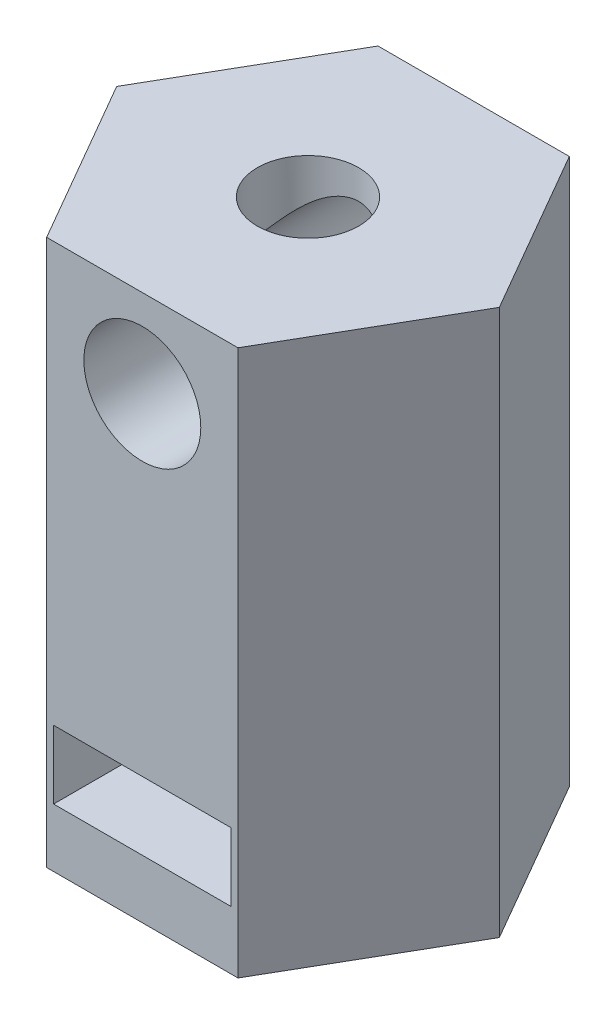
SolidWorks part; units mm, degrees
ref_plane "Front Plane" through (0, 0, 0) normal (0, 0, 1) x (1, 0, 0)
ref_plane "Top Plane" through (0, 0, 0) normal (0, 1, 0) x (1, 0, 0)
ref_plane "Right Plane" through (0, 0, 0) normal (1, 0, 0) x (0, 0, -1)
sketch "Sketch2" plane through (0, 0, 0) normal (0, 1, 0) x (1, 0, 0)
  line L1 (9.815, 0) -> (4.9075, 8.5)
  line L2 (4.9075, 8.5) -> (-4.9075, 8.5)
  line L3 (-4.9075, 8.5) -> (-9.815, 0)
  line L4 (-9.815, 0) -> (-4.9075, -8.5)
  line L5 (-4.9075, -8.5) -> (4.9075, -8.5)
  line L6 (4.9075, -8.5) -> (9.815, 0)
  circle A0 centre (0, 0) radius 8.5 construction
  circle A1 centre (0, 0) radius 2.6
  dimension "D2" = 5.2
  dimension "D1" = 17
extrude "core" add sketch "Sketch2" along normal blind 11
sketch "Sketch5" plane through (0, 0, 8.5) normal (0, 0, 1) x (1, 0, 0)
  line L0 (0, 0) -> (0, 3)
  line L1 (-4.9075, 0) -> (4.9075, 0) construction
  line L2 (4.55, 3) -> (-4.55, 3)
  line L3 (-4.55, 3) -> (4.55, 3)
  line L4 (-4.55, 3) -> (-4.55, 6.5)
  line L5 (4.55, 3) -> (4.55, 6.5)
  line L6 (-4.55, 6.5) -> (4.55, 6.5)
  point P7 (0, 3)
  dimension "D1" = 3
  dimension "D2" = 9.1
  dimension "D3" = 3.5
extrude "hex-nut" cut sketch "Sketch5" against normal blind 14.2 contours L6 L4 L2 L5
sketch "Sketch4" plane through (0, 11, 0) normal (0, 1, 0) x (1, 0, 0)
  line L1 (9.815, 0) -> (4.9075, 8.5)
  line L2 (4.9075, 8.5) -> (-4.9075, 8.5)
  line L3 (-4.9075, 8.5) -> (-9.815, 0)
  line L4 (-9.815, 0) -> (-4.9075, -8.5)
  line L5 (-4.9075, -8.5) -> (4.9075, -8.5)
  line L6 (4.9075, -8.5) -> (9.815, 0)
  circle A0 centre (0, 0) radius 8.5 construction
  circle A1 centre (0, 0) radius 2.6
  dimension "D1" = 5.2
  dimension "D2" = 17
extrude "bolt-guard" add sketch "Sketch4" along normal blind 2 contours L1 L2 L3 L4 L5 L6
sketch "Sketch7" plane through (0, 13, 0) normal (0, 1, 0) x (1, 0, 0)
  line L1 (9.815, 0) -> (4.9075, 8.5)
  line L2 (4.9075, 8.5) -> (-4.9075, 8.5)
  line L3 (-4.9075, 8.5) -> (-9.815, 0)
  line L4 (-9.815, 0) -> (-4.9075, -8.5)
  line L5 (-4.9075, -8.5) -> (4.9075, -8.5)
  line L6 (4.9075, -8.5) -> (9.815, 0)
  circle A0 centre (0, 0) radius 2.6
  circle A1 centre (0, 0) radius 8.5 construction
  dimension "D1" = 5.2
extrude "d-shaft" add sketch "Sketch7" along normal blind 15
sketch "Sketch8" plane through (0, 0, 8.5) normal (0, 0, 1) x (1, 0, 0)
  line L0 (0, 28) -> (0, 23.5)
  line L1 (-4.9075, 28) -> (4.9075, 28) construction
  circle A0 centre (0, 23.5) radius 3
  dimension "D2" = 6
  dimension "D1" = 4.5
extrude "set-screw" cut sketch "Sketch8" against normal through all
sketch "Sketch9" plane through (0, 6.5, 0) normal (0, -1, 0) x (1, 0, 0)
  line L1 (4.55, 0) -> (2.275, 3.9404)
  line L2 (2.275, 3.9404) -> (-2.275, 3.9404)
  line L3 (-2.275, 3.9404) -> (-4.55, 0)
  line L4 (-4.55, 0) -> (-2.275, -3.9404)
  line L5 (-2.275, -3.9404) -> (2.275, -3.9404)
  line L6 (2.275, -3.9404) -> (4.55, 0)
  line L7 (4.55, -5.7) -> (-4.55, -5.7)
  line L8 (4.55, -5.7) -> (4.55, 0)
  line L9 (4.55, 0) -> (-4.55, 0)
  line L10 (-4.55, -5.7) -> (-4.55, 0)
  circle A0 centre (0, 0) radius 3.9404 construction
  line M13 (-4.55, 8.5) -> (-4.55, -5.7)
  line M14 (-4.55, -5.7) -> (4.55, -5.7)
  line M15 (4.55, -5.7) -> (4.55, 8.5)
extrude "Boss-Extrude1" add sketch "Sketch9" along normal through all contours L6 L5 L4 M13 M14 M15
